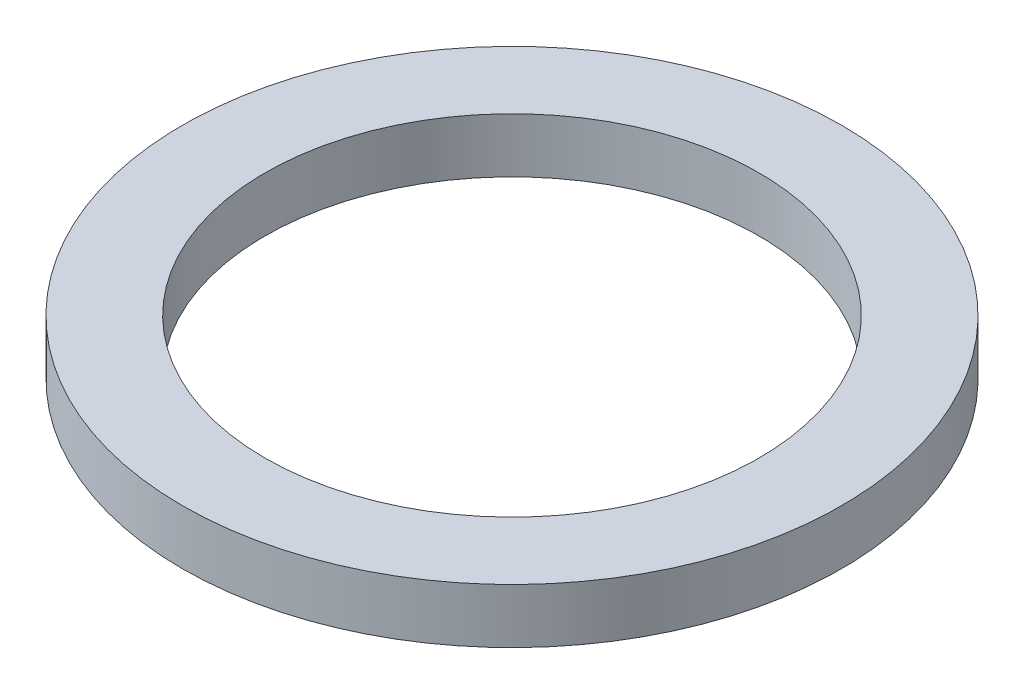
SolidWorks part; units mm, degrees
ref_plane "Front Plane" through (0, 0, 0) normal (0, 0, 1) x (1, 0, 0)
ref_plane "Top Plane" through (0, 0, 0) normal (0, 1, 0) x (1, 0, 0)
ref_plane "Right Plane" through (0, 0, 0) normal (1, 0, 0) x (0, 0, -1)
sketch "Sketch1" plane through (0, 0, 0) normal (0, 1, 0) x (1, 0, 0)
  circle A0 centre (0, 0) radius 38.2905
  circle A1 centre (0, 0) radius 28.702
  dimension "D1" = 57.404
  dimension "D2" = 76.581
extrude "Boss-Extrude1" add sketch "Sketch1" along normal blind 6.35
